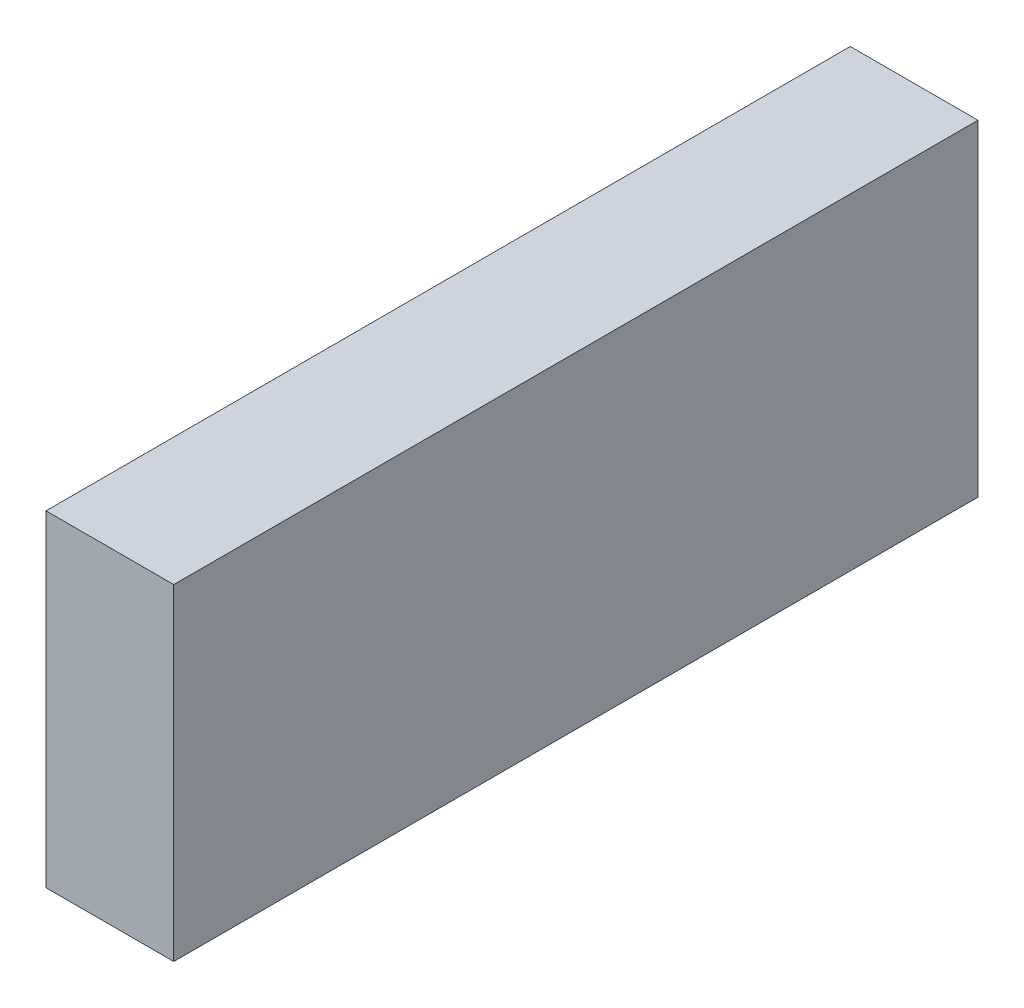
SolidWorks part; units mm, degrees
ref_plane "Front Plane" through (0, 0, 0) normal (0, 0, 1) x (1, 0, 0)
ref_plane "Top Plane" through (0, 0, 0) normal (0, 1, 0) x (1, 0, 0)
ref_plane "Right Plane" through (0, 0, 0) normal (1, 0, 0) x (0, 0, -1)
sketch "Sketch1" plane through (0, 0, 0) normal (1, 0, 0) x (0, 0, -1)
  line L1 (-85, 34.5) -> (85, 34.5)
  line L2 (-85, 34.5) -> (-85, -34.5)
  line L3 (-85, -34.5) -> (85, -34.5)
  line L4 (85, 34.5) -> (85, -34.5)
  line L5 (-85, 34.5) -> (85, -34.5) construction
  line L6 (-85, -34.5) -> (85, 34.5) construction
  point P0 (0, 0)
  dimension "D1" = 69
  dimension "D2" = 170
extrude "Boss-Extrude1" add sketch "Sketch1" along normal blind 27
